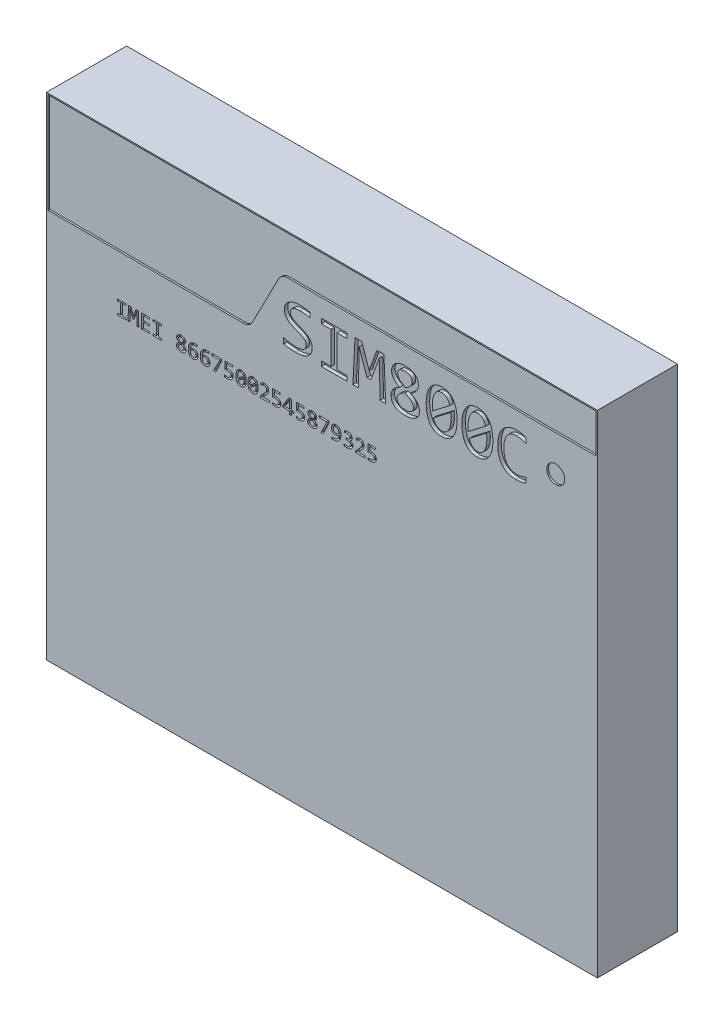
SolidWorks part; units mm, degrees
ref_plane "Horní rovina" through (0, 0, 0) normal (0, 0, 1) x (1, 0, 0)
ref_plane "Přední rovina" through (0, 0, 0) normal (0, 1, 0) x (1, 0, 0)
ref_plane "Pravá rovina" through (0, 0, 0) normal (1, 0, 0) x (0, 0, -1)
sketch "Skica1" plane through (0, 0, 0) normal (0, 0, 1) x (1, 0, 0)
  line L1 (-7.9, 7.05) -> (7.9, 7.05)
  line L2 (-7.9, 7.05) -> (-7.9, -7.05)
  line L3 (-7.9, -7.05) -> (7.9, -7.05)
  line L4 (7.9, 7.05) -> (7.9, -7.05)
  line L5 (-7.9, 7.05) -> (7.9, -7.05) construction
  line L6 (-7.9, -7.05) -> (7.9, 7.05) construction
  point P0 (0, 0)
  dimension "D1" = 14.1
  dimension "D2" = 15.8
extrude "Přidat vysunutím1" add sketch "Skica1" along normal blind 2.3
sketch "Skica2" plane through (0, 0, 2.3) normal (0, 0, 1) x (1, 0, 0)
  line L0 (-1.2003, 4.1827) -> (5.1337, 4.1827) construction
  text T0 "SIM800C" font "Consolas" height 1.2
extrude "Odebrat vysunutím1" cut sketch "Skica2" against normal blind 0.1
sketch "Skica3" plane through (0, 0, 2.3) normal (0, 0, 1) x (1, 0, 0)
  line L0 (-5.9177, 2.5356) -> (2.5771, 2.5356) construction
  text T0 "IMEI 86675002545879325" font "Consolas" height 0.4
extrude "Odebrat vysunutím2" cut sketch "Skica3" against normal blind 0.1
sketch "Skica4" plane through (0, 0, 2.3) normal (0, 0, 1) x (1, 0, 0)
  line L0 (-7.8576, 4.1392) -> (-2.2544, 4.1392)
  line L2 (-1.9878, 4.3017) -> (-1.2472, 5.7376)
  line L3 (-0.9806, 5.9) -> (7.8638, 5.9)
  line L4 (7.8638, 5.9) -> (7.8638, 7.0149)
  line L5 (7.8638, 7.0149) -> (-7.8576, 7.0149)
  line L6 (-7.8576, 7.0149) -> (-7.8576, 4.1392)
  arc A0 (-2.2544, 4.1392) -> (-1.9878, 4.3017) centre (-2.2544, 4.4392) ccw
  arc A1 (-1.2472, 5.7376) -> (-0.9806, 5.9) centre (-0.9806, 5.6) cw
  circle A2 centre (6.7065, 4.8651) radius 0.258
  dimension "D1" = 0.3
extrude "Odebrat vysunutím3" cut sketch "Skica4" against normal blind 0.05
